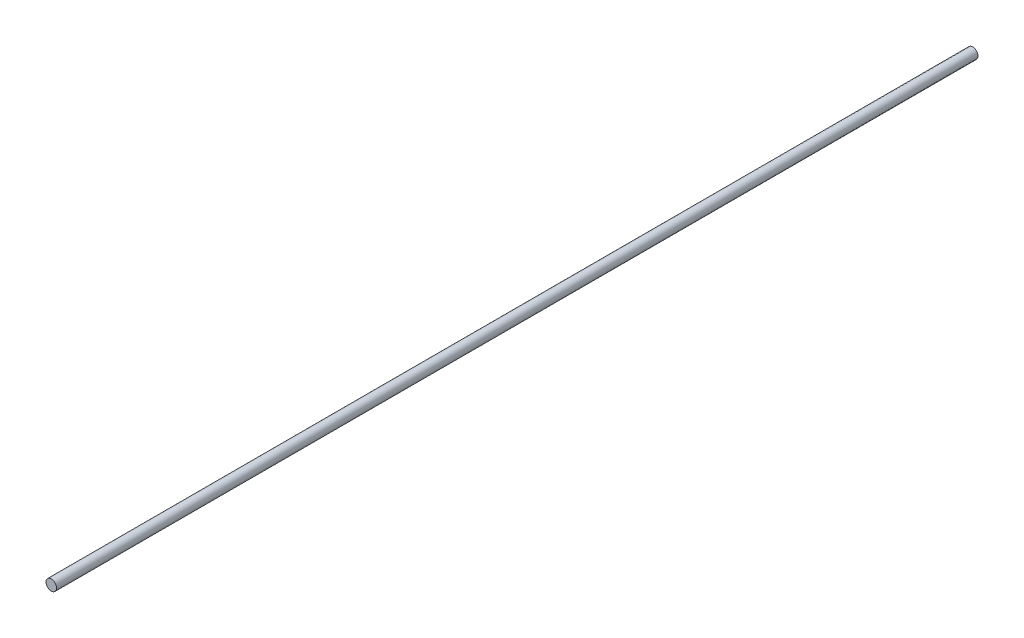
SolidWorks part; units mm, degrees
ref_plane "Alzado" through (0, 0, 0) normal (0, 0, 1) x (1, 0, 0)
ref_plane "Planta" through (0, 0, 0) normal (0, 1, 0) x (1, 0, 0)
ref_plane "Vista lateral" through (0, 0, 0) normal (1, 0, 0) x (0, 0, -1)
sketch "Croquis1" plane through (0, 0, 0) normal (0, 0, 1) x (1, 0, 0)
  circle A0 centre (0, 0) radius 4
  dimension "D1" = 8
extrude "Saliente-Extruir1" add sketch "Croquis1" along normal blind 700
